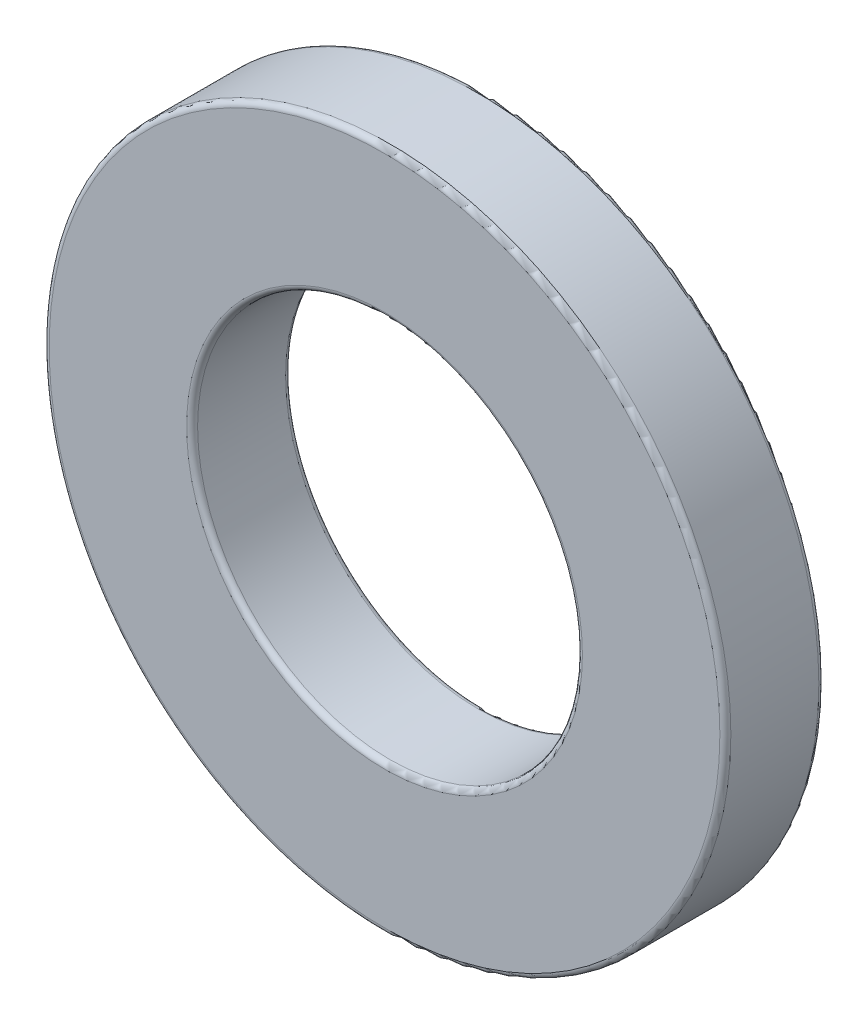
SolidWorks part; units mm, degrees
ref_plane "前视基准面" through (0, 0, 0) normal (0, 0, 1) x (1, 0, 0)
ref_plane "上视基准面" through (0, 0, 0) normal (0, 1, 0) x (1, 0, 0)
ref_plane "右视基准面" through (0, 0, 0) normal (1, 0, 0) x (0, 0, -1)
sketch "草图1" plane through (0, 0, 0) normal (0, 0, 1) x (1, 0, 0)
  circle A0 centre (0, 0) radius 31
  circle A1 centre (0, 0) radius 17.5
extrude "拉伸1" add sketch "草图1" along normal blind 9
fillet "圆角1" radius 0.5 4 edges at (31, 0, 0) (31, 0, 9) (17.5, 0, 0) (17.5, 0, 9)
